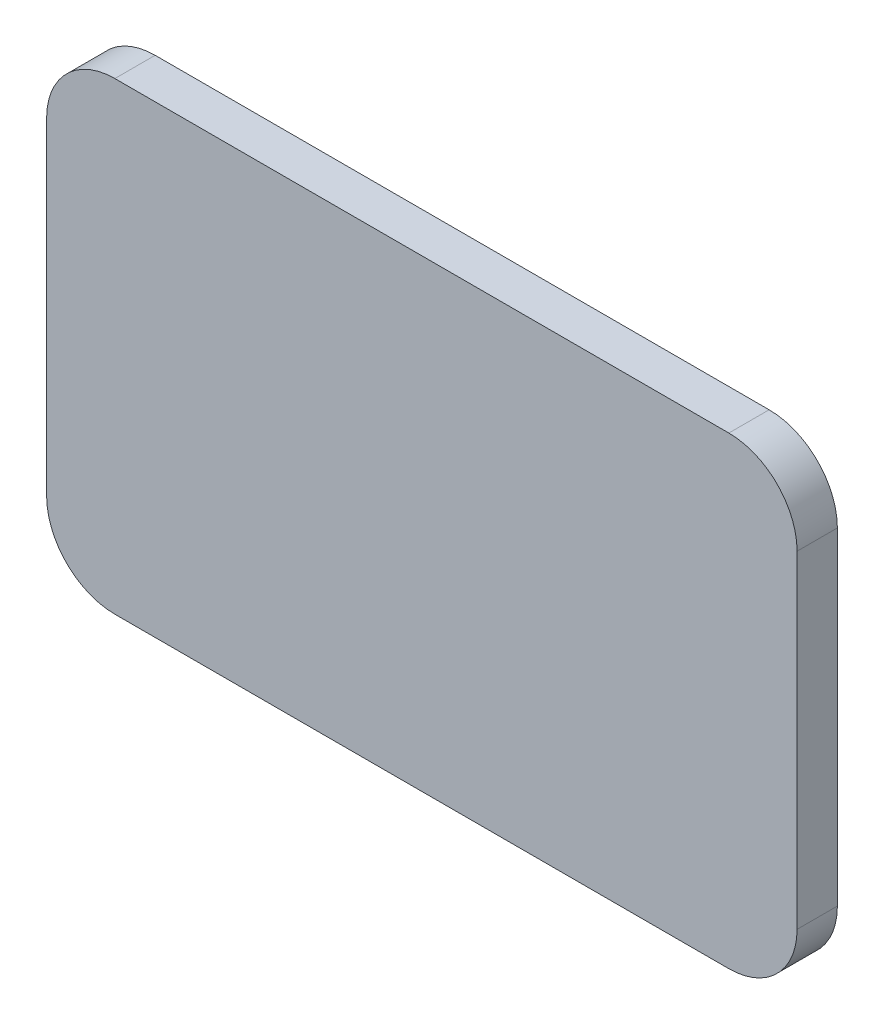
SolidWorks part; units mm, degrees
ref_plane "Alzado" through (0, 0, 0) normal (0, 0, 1) x (1, 0, 0)
ref_plane "Planta" through (0, 0, 0) normal (0, 1, 0) x (1, 0, 0)
ref_plane "Vista lateral" through (0, 0, 0) normal (1, 0, 0) x (0, 0, -1)
sketch "Croquis1" plane through (0, 0, 0) normal (0, 0, 1) x (1, 0, 0)
  line L0 (-0.0361, 20.9923) -> (27.9039, 20.9923) construction
  dimension "D1" = 27.94
sketch "Croquis2" plane through (0, 0, 0) normal (0, 0, 1) x (1, 0, 0)
  line L1 (2.54, 0) -> (25.4, 0)
  line L2 (0, 2.54) -> (0, 14.732)
  line L3 (2.54, 17.272) -> (25.4, 17.272)
  line L4 (27.94, 2.54) -> (27.94, 14.732)
  arc A0 (0, 14.732) -> (2.54, 17.272) centre (2.54, 14.732) cw
  arc A1 (25.4, 17.272) -> (27.94, 14.732) centre (25.4, 14.732) cw
  arc A2 (25.4, 0) -> (27.94, 2.54) centre (25.4, 2.54) ccw
  arc A3 (2.54, 0) -> (0, 2.54) centre (2.54, 2.54) cw
  point P7 (0, 17.272)
  point P10 (27.94, 17.272)
  point P13 (27.94, 0)
  point P16 (0, 0)
  dimension "D3" = 2.54
  dimension "D1" = 27.94
  dimension "D2" = 17.272
extrude "Saliente-Extruir1" add sketch "Croquis2" against normal blind 1.5
sketch "Croquis3" plane through (0, 0, 0) normal (0, 0, 1) x (1, 0, 0)
  line L0 (2.54, 0) -> (25.4, 0) construction
  line L1 (13.97, 17.272) -> (13.97, 0) construction
  line L2 (25.4, 17.272) -> (2.54, 17.272) construction
  line L3 (0, 14.732) -> (0, 2.54) construction
  circle A0 centre (15.24, 2.032) radius 1.016
  circle A1 centre (12.7, 2.032) radius 1.016
  circle A2 centre (10.16, 2.032) radius 1.016
  circle A3 centre (7.62, 2.032) radius 1.016
  circle A4 centre (5.08, 2.032) radius 1.016
  circle A5 centre (2.54, 2.032) radius 1.016
  circle A6 centre (2.54, 14.478) radius 1.905
  circle A7 centre (2.54, 14.478) radius 1.294
  dimension "D1" = 2.032
  dimension "D2" = 2.032
  dimension "D6" = 3.81
  dimension "D7" = 22.86
  dimension "D8" = 14.478
  dimension "D3" = 2.54
  dimension "D5" = 2.54
  dimension "D9" = 2.54
  dimension "D4" = 6
